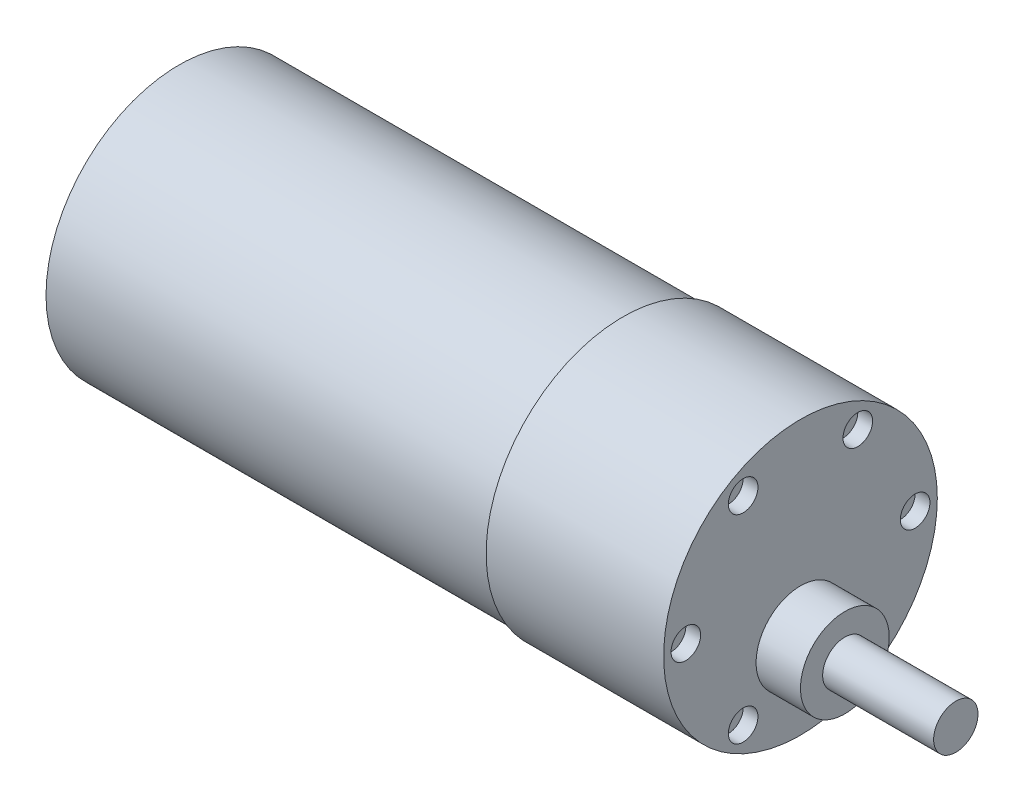
SolidWorks part; units mm, degrees
ref_plane "Front Plane" through (0, 0, 0) normal (0, 0, 1) x (1, 0, 0)
ref_plane "Top Plane" through (0, 0, 0) normal (0, 1, 0) x (1, 0, 0)
ref_plane "Right Plane" through (0, 0, 0) normal (1, 0, 0) x (0, 0, -1)
sketch "Sketch1" plane through (0, 0, 0) normal (1, 0, 0) x (0, 0, -1)
  circle A0 centre (0, 0) radius 18.5
  circle A1 centre (0, -7) radius 6 construction
  circle A2 centre (-15.5, 0) radius 2 construction
  circle A3 centre (-7.75, 13.4234) radius 2 construction
  circle A4 centre (7.75, 13.4234) radius 2 construction
  circle A5 centre (15.5, 0) radius 2 construction
  circle A6 centre (7.75, -13.4234) radius 2 construction
  circle A7 centre (-7.75, -13.4234) radius 2 construction
  point P19 (0, 0)
  dimension "D1" = 37
  dimension "D3" = 12
  dimension "D4" = 15.5
  dimension "D5" = 4
  dimension "D2" = 7
  dimension "D6" = 6
extrude "Boss-Extrude1" add sketch "Sketch1" against normal blind 24
sketch "Sketch2" plane through (-24, 0, 0) normal (-1, 0, 0) x (0, 0, 1)
  circle A0 centre (0, 0) radius 18
extrude "Boss-Extrude2" add sketch "Sketch2" along normal blind 60
sketch "Sketch3" plane through (0, 0, 0) normal (1, 0, 0) x (0, 0, -1)
  line L0 (0, 0) -> (0, -7) construction
  circle A1 centre (0, -7) radius 6
  dimension "D2" = 12
  dimension "D1" = 7
extrude "Boss-Extrude3" add sketch "Sketch3" along normal blind 6
sketch "Sketch4" plane through (6, 0, 0) normal (1, 0, 0) x (0, 0, -1)
  circle A0 centre (0, -7) radius 3
  dimension "D1" = 6
extrude "Boss-Extrude4" add sketch "Sketch4" along normal blind 15
sketch "Sketch5" plane through (0, 0, 0) normal (1, 0, 0) x (0, 0, -1)
  circle A0 centre (-15.5, 0) radius 2
  circle A1 centre (-7.75, 13.4234) radius 2
  circle A2 centre (7.75, 13.4234) radius 2
  circle A3 centre (15.5, 0) radius 2
  circle A4 centre (7.75, -13.4234) radius 2
  circle A5 centre (-7.75, -13.4234) radius 2
  point P15 (0, 0)
  dimension "D2" = 4
  dimension "D1" = 15.5
  dimension "D3" = 6
extrude "Cut-Extrude1" cut sketch "Sketch5" against normal blind 2
